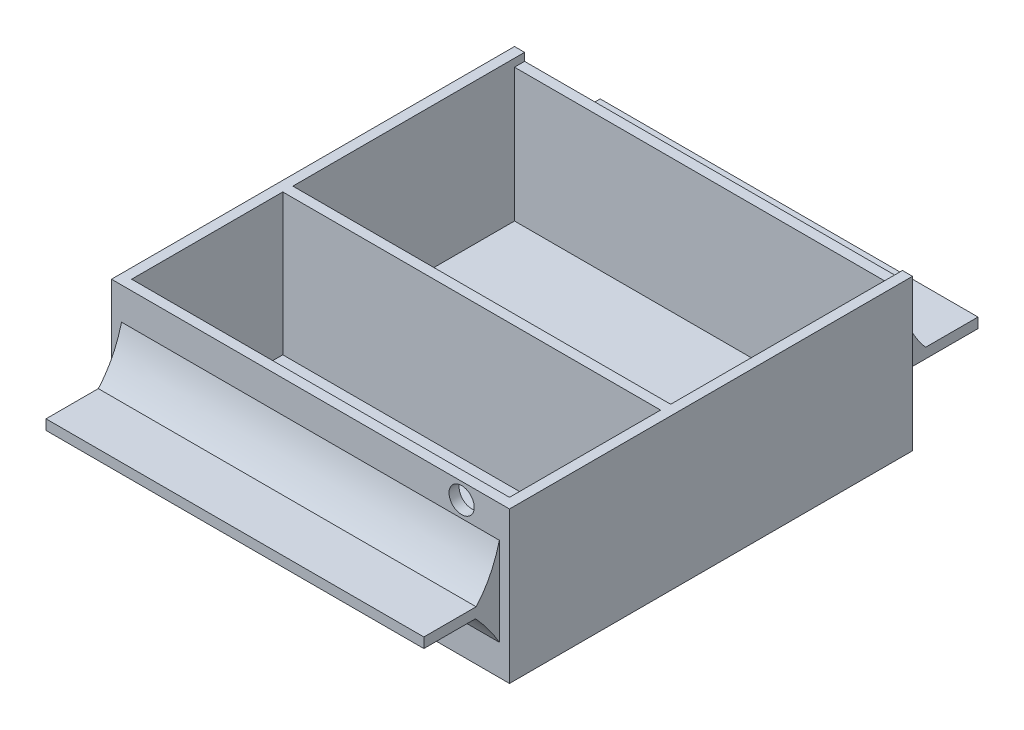
SolidWorks part; units mm, degrees
ref_plane "前视基准面" through (0, 0, 0) normal (0, 0, 1) x (1, 0, 0)
ref_plane "上视基准面" through (0, 0, 0) normal (0, 1, 0) x (1, 0, 0)
ref_plane "右视基准面" through (0, 0, 0) normal (1, 0, 0) x (0, 0, -1)
sketch "草图1" plane through (0, 0, 0) normal (1, 0, 0) x (0, 0, -1)
  line L0 (30, 31) -> (30, 0)
  line L1 (0, 0) -> (30, 0)
  line L2 (0, 0) -> (0, -4)
  line L3 (0, -4) -> (30, -4)
  line L4 (98, -25) -> (186, -25)
  line L5 (30, -29) -> (190, -29)
  line L6 (190, 27.8926) -> (190, -29)
  line L7 (34, 31) -> (34, -25)
  line L8 (34, -25) -> (94, -25)
  line L9 (186, -25) -> (186, 27.8926)
  line L10 (186, 27.8926) -> (190, 27.8926)
  line L11 (34, 31) -> (30, 31)
  line L12 (94, 31) -> (94, -25)
  line L14 (98, -25) -> (98, 31)
  line L15 (98, 31) -> (94, 31)
  line L16 (94, 31) -> (93.6579, 30.6978)
  line L17 (30, -4) -> (30, -29)
  dimension "D1" = 30
  dimension "D2" = 4
  dimension "D3" = 25
  dimension "D4" = 160
  dimension "D5" = 60
  dimension "D6" = 4
  dimension "D7" = 4
  dimension "D8" = 4
  dimension "D9" = 4
  dimension "D10" = 60
extrude "凸台-拉伸1" add sketch "草图1" along normal blind 150 contours L12 L8 L7 L11 L0 L1 L2 L3 L17 L5 L6 L10 L9 L4 L14 L15
sketch "草图2" plane through (150, 0, 0) normal (1, 0, 0) x (0, 0, -1)
  line L1 (30, 31) -> (190, 31)
  line L2 (30, 31) -> (30, -29)
  line L3 (30, -29) -> (190, -29)
  line L4 (190, 31) -> (190, -29)
extrude "凸台-拉伸2" add sketch "草图2" along normal blind 4
sketch "草图3" plane through (0, 0, 0) normal (-1, 0, 0) x (0, 0, 1)
  line L1 (-190, 31) -> (-30, 31)
  line L2 (-190, 31) -> (-190, -29)
  line L3 (-190, -29) -> (-30, -29)
  line L4 (-30, 31) -> (-30, -29)
extrude "凸台-拉伸3" add sketch "草图3" along normal blind 4
ref_plane "基准面1" through (150, 0, -30) normal (-1, 0, 0) x (0, 0, 1)
sketch "草图5" plane through (150, 0, -30) normal (-1, 0, 0) x (0, 0, 1)
  line L0 (0, -29) -> (0, 31) construction
  line L1 (0, 18.235) -> (2.8377, 7.0928) construction
  line L2 (2.8377, 7.0928) -> (9.2386, 0) construction
  line L3 (30, 0) -> (0, 0) construction
  line L4 (0, -16.851) -> (3.6675, -10.3317) construction
  line L6 (30, -4) -> (0, -4) construction
  line L7 (3.6675, -10.3317) -> (9.4756, -4) construction
  line L8 (0, 18.235) -> (0, 0)
  line L9 (0, 0) -> (9.3388, -0.0929)
  line L10 (9.2386, 0) -> (9.3388, -0.0929)
  line L11 (9.3388, -0.0929) -> (9.5445, 0.1084)
  line L12 (9.4756, -4) -> (0, -4)
  line L13 (0, -4) -> (0, -16.851)
  spline S0 degree 2 poles (0, 18.235) (2.8377, 7.0928) (9.2386, 0) knots 0 0 0 1 1 1
  spline S1 degree 2 poles (0, -16.851) (3.6675, -10.3317) (9.4756, -4) knots 0 0 0 1 1 1
extrude "凸台-拉伸5" add sketch "草图5" along normal up to surface (150 mm away) contours S0 L8 L9 L10 | L13 S1 L12 up to face at (0, -2, -15)
sketch "草图6" plane through (0, 31, 0) normal (0, 1, 0) x (1, 0, 0)
  line L0 (154, 30) -> (154, 190) construction
  point P4 (154, 110)
ref_plane "基准面2" through (0, 0, -110) normal (0, 0, 1) x (1, 0, 0)
mirror "镜向2" about plane through (0, 0, -110) normal (0, 0, 1) of "凸台-拉伸5"
sketch "草图8" plane through (150, 0, 0) normal (1, 0, 0) x (0, 0, -1)
  line L0 (190, 0) -> (220, 0)
  line L1 (190, 0) -> (190, -4)
  line L2 (190, -4) -> (220, -4)
  line L3 (220, -4) -> (220, 0)
  dimension "D1" = 30
extrude "凸台-拉伸6" add sketch "草图8" against normal up to surface (150 mm away) up to face at (0, 2.2562, -195.7992)
sketch "草图9" plane through (150, 0, 0) normal (1, 0, 0) x (0, 0, -1)
  line L0 (199.4756, -4) -> (190, -4)
  line L1 (190, -29) -> (190, 31) construction
  line L2 (190, -4) -> (190, -16.851)
  line L3 (190, -16.851) -> (199.4756, -4)
extrude "切除-拉伸1" cut sketch "草图9" against normal up to next
sketch "草图10" plane through (0, 0, -98) normal (0, 0, -1) x (-1, 0, 0)
  circle A0 centre (-137.2889, 2.6256) radius 10
  dimension "D1" = 20
extrude "切除-拉伸2" cut sketch "草图10" against normal blind 10
sketch "草图11" plane through (0, 0, -30) normal (0, 0, 1) x (1, 0, 0)
  circle A0 centre (134.9991, 24.5597) radius 5
  dimension "D1" = 10
extrude "切除-拉伸3" cut sketch "草图11" against normal blind 10
